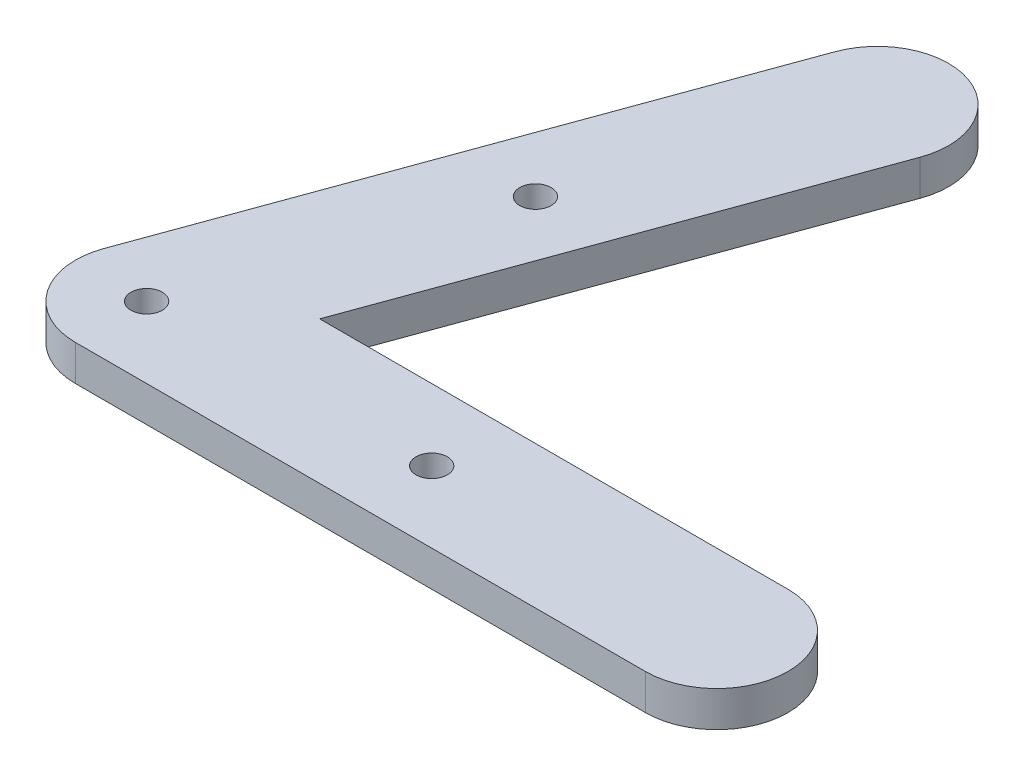
SolidWorks part; units mm, degrees
ref_plane "Front" through (0, 0, 0) normal (0, 0, 1) x (1, 0, 0)
ref_plane "Top" through (0, 0, 0) normal (0, 1, 0) x (1, 0, 0)
ref_plane "Right" through (0, 0, 0) normal (1, 0, 0) x (0, 0, -1)
sketch "Sketch5" plane through (0, 0, 0) normal (0, 1, 0) x (1, 0, 0)
  line L0 (0, 0) -> (101.6, 0) construction
  line L1 (0, 12.7) -> (101.6, 12.7)
  line L2 (0, -12.7) -> (101.6, -12.7)
  line L3 (0, 0) -> (34.7492, 95.4728) construction
  line L4 (-11.9341, 4.3437) -> (22.8152, 99.8164)
  line L5 (11.9341, -4.3437) -> (46.6833, 91.1291)
  line L12 (-11.9341, 4.3437) -> (22.8152, 99.8164)
  line L13 (46.6833, 91.1291) -> (18.1375, 12.7)
  arc A0 (0, 12.7) -> (0, -12.7) centre (0, 0) ccw
  arc A1 (101.6, -12.7) -> (101.6, 12.7) centre (101.6, 0) ccw
  arc A2 (-11.9341, 4.3437) -> (11.9341, -4.3437) centre (0, 0) ccw
  arc A3 (46.6833, 91.1291) -> (22.8152, 99.8164) centre (34.7492, 95.4728) ccw
  circle A6 centre (0, 0) radius 2.794
  point P3 (50.8, 0)
  point P8 (17.3746, 47.7364)
  dimension "D1" = 70
extrude "Boss-Extrude21" add sketch "Sketch5" along normal blind 6.35 contours A2 L2 A1 L1 L5 | L5 A3 L4 A0 L1 | A0 A2 L5 L1 A6
sketch "Sketch6" plane through (0, 0, 0) normal (0, -1, 0) x (-1, 0, 0)
  line L0 (11.9341, 4.3437) -> (-22.8152, 99.8164) construction
  circle A0 centre (-50.8, 0) radius 2.794
  circle A1 centre (-18.4897, 50.8) radius 2.794
  circle A2 centre (0, 0) radius 2.794 construction
  dimension "D1" = 5.588
  dimension "D2" = 5.588
  dimension "D3" = 50.8
  dimension "D4" = 50.8
  dimension "D5" = 12.7
extrude "Cut-Extrude3" cut sketch "Sketch6" against normal blind 6.35
